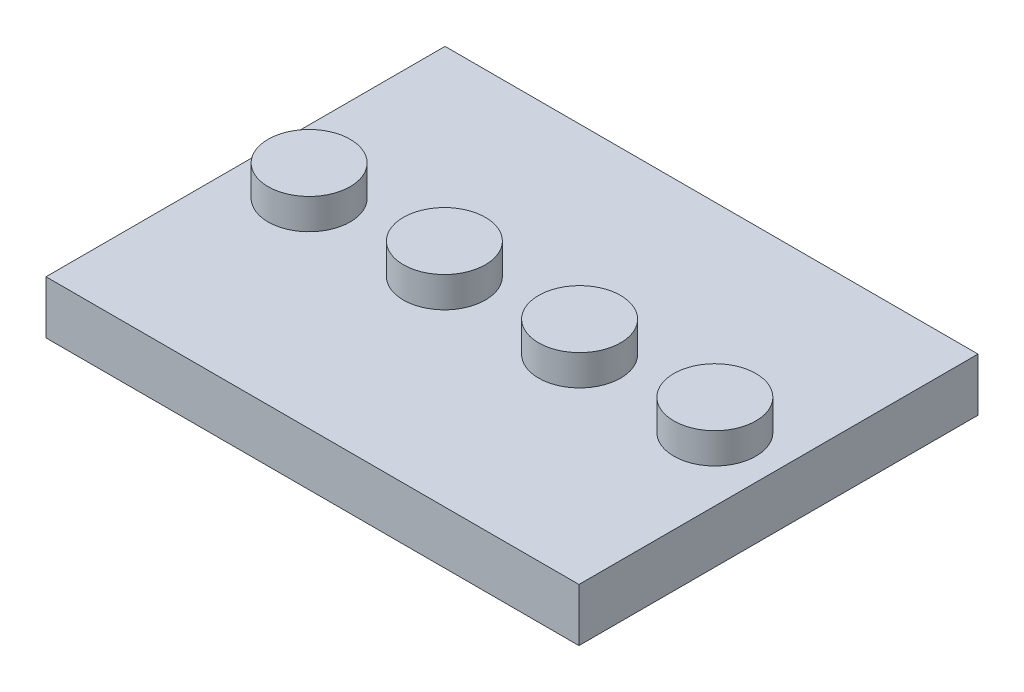
SolidWorks part; units mm, degrees
ref_plane "Front Plane" through (0, 0, 0) normal (0, 0, 1) x (1, 0, 0)
ref_plane "Top Plane" through (0, 0, 0) normal (0, 1, 0) x (1, 0, 0)
ref_plane "Right Plane" through (0, 0, 0) normal (1, 0, 0) x (0, 0, -1)
sketch "Sketch2" plane through (0, 0, 0) normal (0, 1, 0) x (1, 0, 0)
  line L0 (0, 19.7158) -> (0, -20.5071) construction
  line L1 (-15.94, 11.935) -> (15.94, 11.935)
  line L2 (-15.94, 11.935) -> (-15.94, -11.935)
  line L3 (-15.94, -11.935) -> (15.94, -11.935)
  line L4 (15.94, 11.935) -> (15.94, -11.935)
  line L5 (-15.94, 11.935) -> (15.94, -11.935) construction
  line L6 (-15.94, -11.935) -> (15.94, 11.935) construction
  point P0 (0, 0)
  dimension "D1" = 23.87
  dimension "D2" = 31.88
extrude "Boss-Extrude1" add sketch "Sketch2" against normal blind 3.17
sketch "Sketch3" plane through (0, 0, 0) normal (0, 1, 0) x (1, 0, 0)
  line L1 (15.94, 11.935) -> (-15.94, 11.935) construction
  circle A0 centre (-12.135, 0) radius 2.455
  circle A1 centre (-4.045, 0) radius 2.455
  circle A2 centre (4.045, 0) radius 2.455
  circle A3 centre (12.135, 0) radius 2.455
  dimension "D1" = 4.91
  dimension "D3" = 8.09
  dimension "D4" = 8.09
  dimension "D5" = 8.09
  dimension "D6" = 4.045
  dimension "D2" = 11.935
extrude "Boss-Extrude2" add sketch "Sketch3" along normal blind 1.83
shell "Shell1" thickness 1.5
sketch "Sketch4" plane through (0, -1.5, 0) normal (0, -1, 0) x (1, 0, 0)
  line L1 (-15.94, 11.935) -> (15.94, 11.935) construction
  line L2 (-15.94, -11.935) -> (-15.94, 11.935) construction
  line L3 (15.94, 11.935) -> (15.94, -11.935) construction
  circle A0 centre (-7.97, 3.9783) radius 3.24
  circle A1 centre (-7.97, 3.9783) radius 2.41
  circle A2 centre (0, 3.9783) radius 2.41
  circle A3 centre (0, 3.9783) radius 3.24
  circle A4 centre (7.97, 3.9783) radius 2.41
  circle A5 centre (7.97, 3.9783) radius 3.24
  circle A6 centre (0, -3.9817) radius 2.41
  circle A7 centre (0, -3.9817) radius 3.24
  circle A8 centre (7.97, -3.9817) radius 2.41
  circle A9 centre (7.97, -3.9817) radius 3.24
  circle A10 centre (-7.97, -3.9817) radius 2.41
  circle A11 centre (-7.97, -3.9817) radius 3.24
  dimension "D1" = 6.48
  dimension "D2" = 4.82
  dimension "D7" = 7.96
  dimension "D8" = 7.97
  dimension "D9" = 7.97
  dimension "D3" = 7.9567
  dimension "D4" = 7.97
  dimension "D5" = 3
  dimension "D6" = 2
extrude "Boss-Extrude3" add sketch "Sketch4" along normal offset from surface (1.47 mm away) 0.2 up to face at (0, -3.17, 0)
